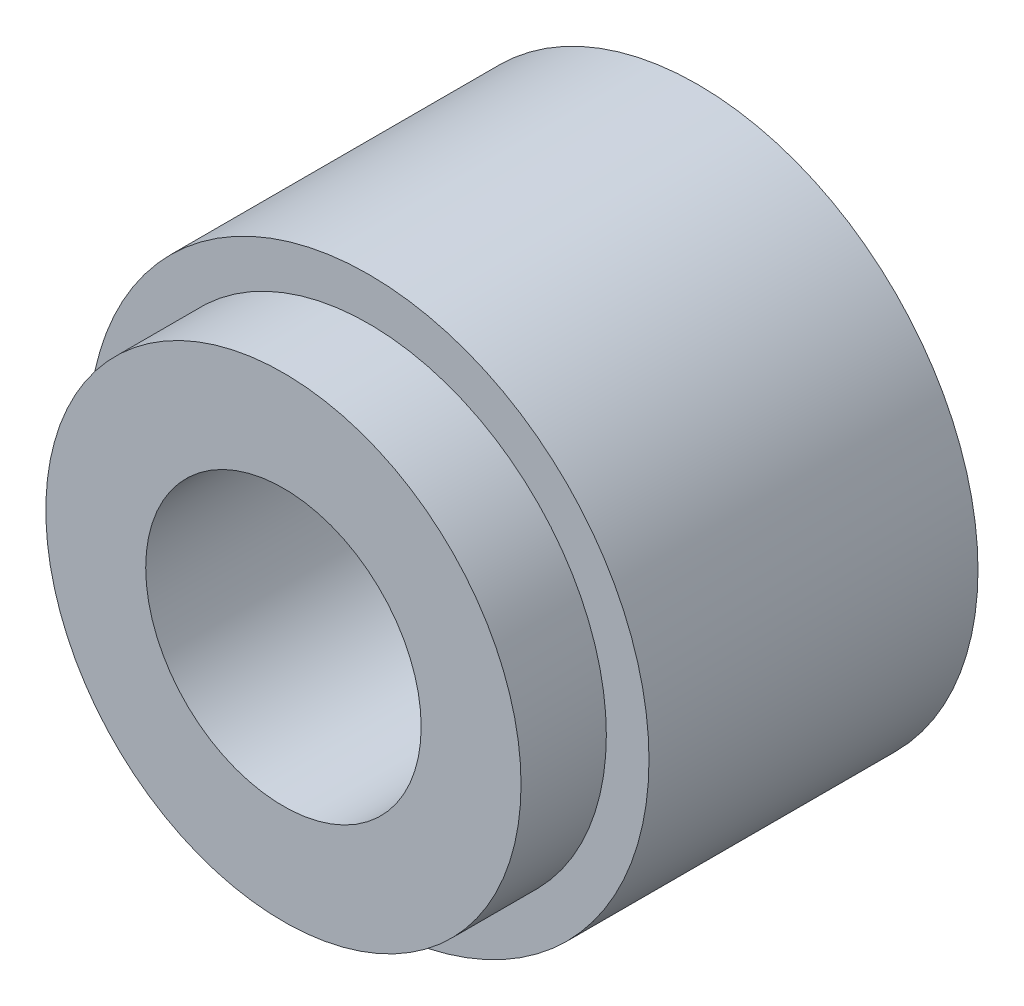
SolidWorks part; units mm, degrees
ref_plane "Face" through (0, 0, 0) normal (0, 0, 1) x (1, 0, 0)
ref_plane "Dessus" through (0, 0, 0) normal (0, 1, 0) x (1, 0, 0)
ref_plane "Droite" through (0, 0, 0) normal (1, 0, 0) x (0, 0, -1)
sketch "Esquisse1" plane through (0, 0, 0) normal (0, 0, 1) x (1, 0, 0)
  circle A0 centre (0, 0) radius 2.3
  dimension "D1" = 4.6
extrude "Extrusion1" add sketch "Esquisse1" along normal blind 2.7
sketch "Esquisse2" plane through (0, 0, 2.7) normal (0, 0, 1) x (1, 0, 0)
  circle A0 centre (0, 0) radius 1.95
  dimension "D1" = 3.9
extrude "Extrusion2" add sketch "Esquisse2" along normal blind 0.7
hole_wizard "#4-40 Tapped Hole1" positions "Esquisse3D1" profile "Esquisse4" tap size "#4-40" standard "Ansi Inch" end condition through all
sketch3d "Esquisse3D1"
  point P9 (0, 0, 3.4)
cosmetic thread "Filetage de perçage1" parameters "D2"=2.8448
sketch "Esquisse4" plane through (0, 0, 3.4) normal (1, 0, 0) x (0, -1, 0)
  line L0 (0, 0) -> (0, 3.4)
  line L1 (0, 3.4) -> (1.27, 3.4)
  line L2 (1.1303, 3.2603) -> (1.1303, 0)
  line L5 (1.1303, 0) -> (0, 0)
  line L7 (1.27, 3.4) -> (1.1303, 3.2603)
  line L8 (-1.27, 3.4) -> (-1.1303, 3.2603) construction
  line L11 (0, -6.35) -> (0, 107.95) construction
  dimension "Thru Tap Drill Dia." = 2.2606
  dimension "Thru Tap Drill Depth" = 3.4
  dimension "Far C'Sink Dia." = 2.54
  dimension "Far C'Sink Angle" = 90
